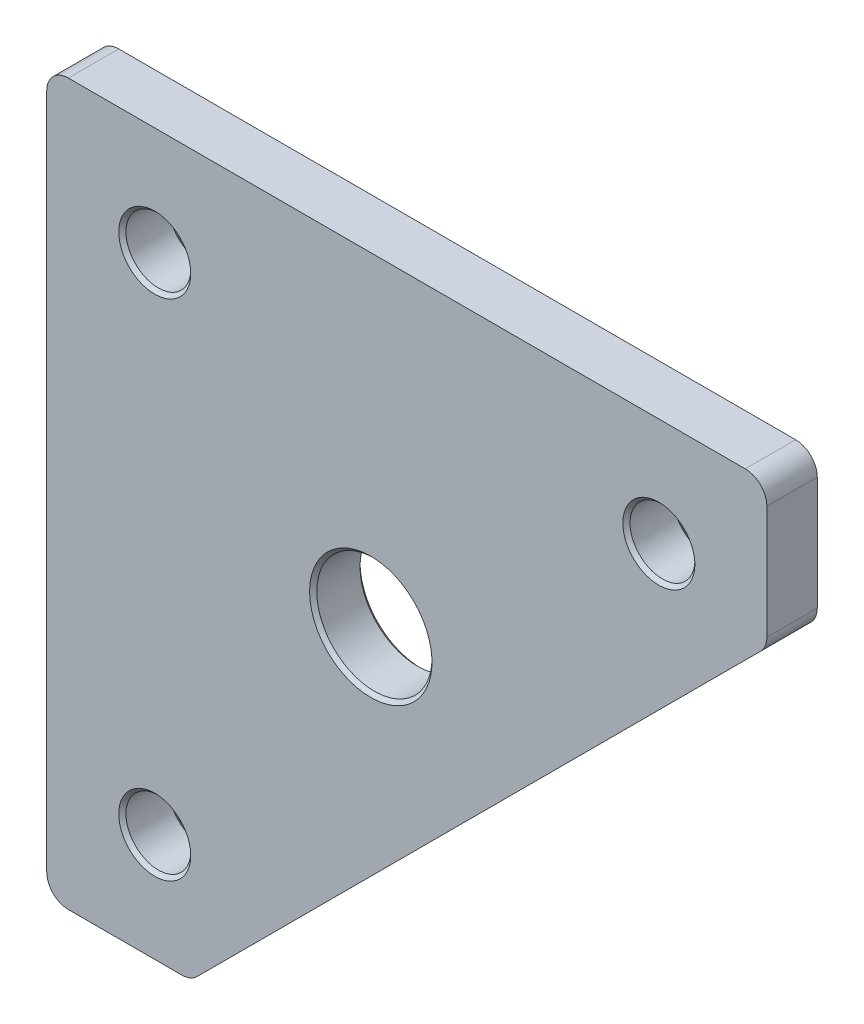
SolidWorks part; units mm, degrees
ref_plane "Front Plane" through (0, 0, 0) normal (0, 0, 1) x (1, 0, 0)
ref_plane "Top Plane" through (0, 0, 0) normal (0, 1, 0) x (1, 0, 0)
ref_plane "Right Plane" through (0, 0, 0) normal (1, 0, 0) x (0, 0, -1)
ref_plane "Plane1" through (0, 0, 0) normal (0, 0, -1) x (-1, 0, 0)
sketch "Sketch1" plane through (0, 0, 0) normal (0, 0, -1) x (-1, 0, 0)
  line L0 (0, 0) -> (-100, 0)
  line L1 (-100, 0) -> (-100, -20)
  line L2 (-100, -20) -> (-20, -100)
  line L3 (-20, -100) -> (0, -100)
  line L4 (0, -100) -> (0, 0)
extrude "Boss-Extrude1" add sketch "Sketch1" against normal blind 7
hole_wizard "Ø9.0 (9) Diameter Hole1" positions "Sketch3" profile "Sketch2" hole size "Ø9.0" standard "ANSI Metric"
sketch "Sketch3" plane through (0, 0, 7) normal (0, 0, 1) x (1, 0, 0)
  point P0 (85, -15)
  point P1 (15, -15)
sketch "Sketch2" plane through (85, -15, 7) normal (1, 0, 0) x (0, -1, 0)
  line L0 (0, 0) -> (0, 7)
  line L1 (0, 7) -> (4.5, 7)
  line L2 (4.5, 7) -> (4.5, 0)
  line L5 (4.5, 0) -> (0, 0)
  line L11 (0, -6.35) -> (0, 107.95) construction
  dimension "Thru Hole Dia." = 9
  dimension "Thru Hole Depth" = 7
hole_wizard "Ø16.0 (16) Diameter Hole1" positions "Sketch5" profile "Sketch4" hole size "Ø16.0" standard "ANSI Metric"
sketch "Sketch5" plane through (0, 0, 7) normal (0, 0, 1) x (1, 0, 0)
  point P0 (45, -45)
sketch "Sketch4" plane through (45, -45, 7) normal (1, 0, 0) x (0, -1, 0)
  line L0 (0, 0) -> (0, 7)
  line L1 (0, 7) -> (8, 7)
  line L2 (8, 7) -> (8, 0)
  line L5 (8, 0) -> (0, 0)
  line L11 (0, -6.35) -> (0, 107.95) construction
  dimension "Thru Hole Dia." = 16
  dimension "Thru Hole Depth" = 7
hole_wizard "Ø9.0 (9) Diameter Hole2" positions "Sketch7" profile "Sketch6" hole size "Ø9.0" standard "ANSI Metric"
sketch "Sketch7" plane through (0, 0, 0) normal (0, 0, -1) x (-1, 0, 0)
  point P0 (-15, -85)
sketch "Sketch6" plane through (15, -85, 0) normal (1, 0, 0) x (0, 1, 0)
  line L0 (0, 0) -> (0, 7)
  line L1 (0, 7) -> (4.5, 7)
  line L2 (4.5, 7) -> (4.5, 0)
  line L5 (4.5, 0) -> (0, 0)
  line L11 (0, -6.35) -> (0, 107.95) construction
  dimension "Thru Hole Dia." = 9
  dimension "Thru Hole Depth" = 7
chamfer "Chamfer1" distance 0.5 angle 45 8 edges at (89.5, -15, 0) (10.5, -85, 7) (53, -45, 0) (10.5, -85, 0) (19.5, -15, 0) (19.5, -15, 7) (53, -45, 7) (89.5, -15, 7)
fillet "Fillet1" radius 3 5 edges at (0, -100, 3.5) (0, 0, 3.5) (20, -100, 3.5) (100, -20, 3.5) (100, 0, 3.5)
